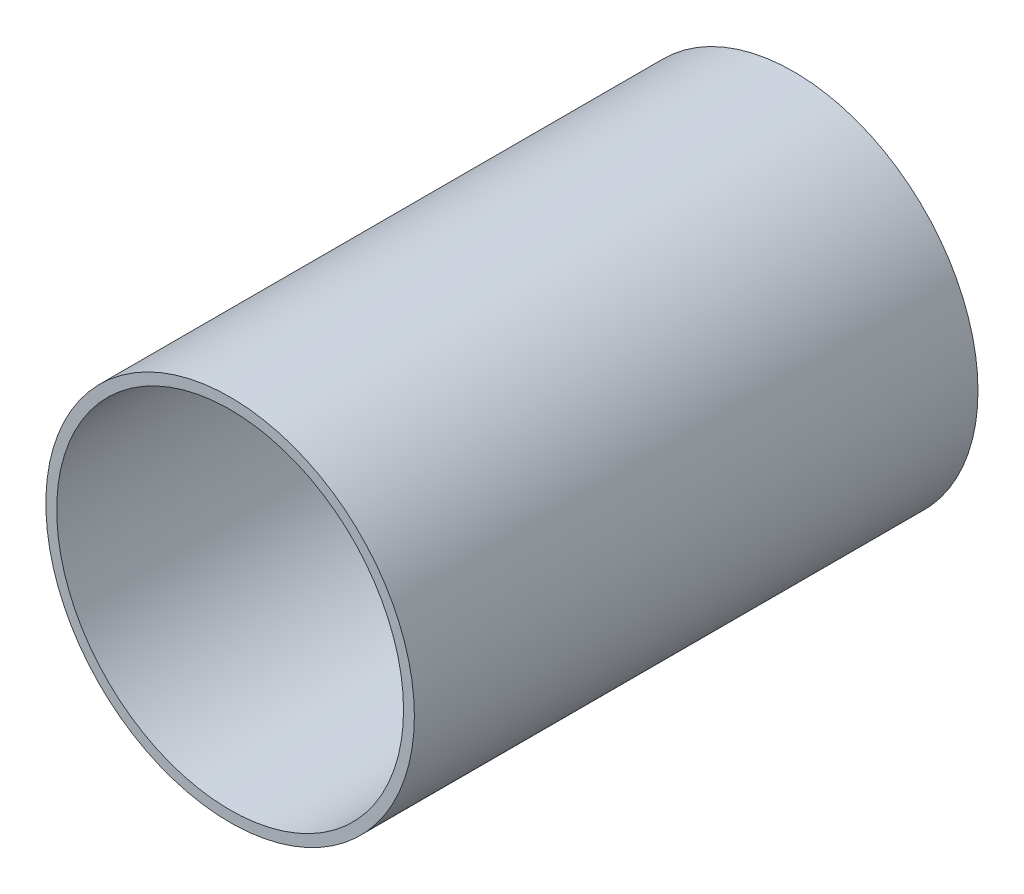
SolidWorks part; units mm, degrees
ref_plane "Front Plane" through (0, 0, 0) normal (0, 0, 1) x (1, 0, 0)
ref_plane "Top Plane" through (0, 0, 0) normal (0, 1, 0) x (1, 0, 0)
ref_plane "Right Plane" through (0, 0, 0) normal (1, 0, 0) x (0, 0, -1)
sketch "Sketch1" plane through (0, 0, 0) normal (0, 0, 1) x (1, 0, 0)
  circle A0 centre (0, 0) radius 8.5
  dimension "D1" = 17
extrude "Boss-Extrude1" add sketch "Sketch1" along normal blind 1
sketch "Sketch2" plane through (0, 0, 1) normal (0, 0, 1) x (1, 0, 0)
  circle A0 centre (0, 0) radius 8.5
  circle A1 centre (0, 0) radius 8
  circle A2 centre (0, 0) radius 8.5 construction
  dimension "D1" = 0.5
extrude "Boss-Extrude2" add sketch "Sketch2" along normal blind 25
chamfer "Chamfer1" distance 1 angle 45 1 edges at (8, 0, 1)
